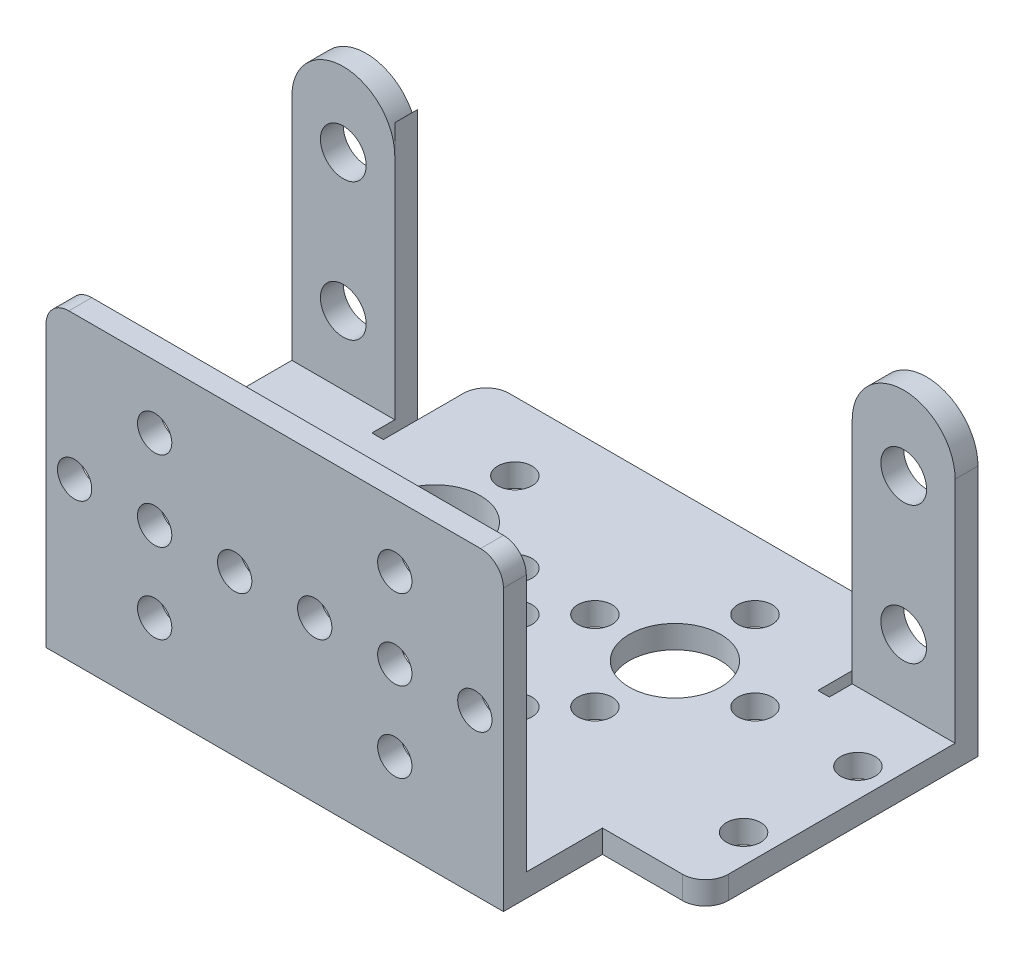
SolidWorks part; units mm, degrees
ref_plane "前视基准面" through (0, 0, 0) normal (0, 0, 1) x (1, 0, 0)
ref_plane "上视基准面" through (0, 0, 0) normal (0, 1, 0) x (1, 0, 0)
ref_plane "右视基准面" through (0, 0, 0) normal (1, 0, 0) x (0, 0, -1)
sketch "草图1" plane through (0, 0, 0) normal (0, 1, 0) x (1, 0, 0)
  line L1 (29, -18.75) -> (-29, -18.75)
  line L2 (29, -18.75) -> (29, 18.75)
  line L3 (29, 18.75) -> (-29, 18.75)
  line L4 (-29, -18.75) -> (-29, 18.75)
  line L5 (29, -18.75) -> (-29, 18.75) construction
  line L6 (29, 18.75) -> (-29, -18.75) construction
  point P0 (0, 0)
  dimension "D1" = 37.5
  dimension "D2" = 58
extrude "凸台-拉伸1" add sketch "草图1" along normal blind 26.5
sketch "草图3" plane through (29, 0, 0) normal (1, 0, 0) x (0, 0, -1)
  line L0 (13.75, 2) -> (22.2889, 2)
  line L2 (-16.75, 2) -> (-16.75, 27.3196)
  line L3 (-16.75, 27.3196) -> (11.75, 27.3196)
  line L4 (11.75, 27.3196) -> (11.75, 2)
  line L7 (13.75, 2) -> (13.75, 26.5)
  line L8 (-18.75, 26.5) -> (18.75, 26.5) construction
  line L9 (13.75, 26.5) -> (22.2889, 26.5)
  line L10 (22.2889, 26.5) -> (22.2889, 2)
  line L14 (-16.75, 2) -> (11.75, 2)
extrude "切除-拉伸1" cut sketch "草图3" against normal through all
sketch "草图4" plane through (0, 2, 0) normal (0, 1, 0) x (1, 0, 0)
  line L0 (-29, 13.75) -> (-20, 13.75)
  line L1 (-29, 18.75) -> (29, 18.75)
  line L2 (29, 18.75) -> (29, 13.75)
  line L3 (0, 23.209) -> (0, -24.1178) construction
  line L6 (-29, -16.75) -> (-29, 11.75) construction
  line L8 (-20, 13.75) -> (-20, 9.75)
  line L9 (-20, 9.75) -> (-19, 9.75)
  line L10 (-19, 9.75) -> (-19, 16.75)
  line L11 (-29, 18.75) -> (29, 18.75) construction
  line L12 (-17, 18.75) -> (17, 18.75)
  line L13 (19, 16.75) -> (19, 9.75)
  line L14 (19, 9.75) -> (20, 9.75)
  line L15 (20, 9.75) -> (20, 13.75)
  line L16 (-29, 13.75) -> (29, 13.75) construction
  line L17 (20, 13.75) -> (29, 13.75)
  line L18 (-29, 13.75) -> (-29, 18.75)
  line L23 (20, -10.0868) -> (27, -10.0868)
  line L24 (-20, -10.0868) -> (-20, -21.4924)
  line L26 (-20, -10.0868) -> (-27, -10.0868)
  line L27 (-20, -21.4924) -> (-29, -21.4924)
  line L28 (-29, -21.4924) -> (-29, -8.0868)
  line L29 (20, -10.0868) -> (20, -21.4924)
  line L30 (20, -21.4924) -> (29, -21.4924)
  line L31 (29, -21.4924) -> (29, -8.0868)
  arc A0 (17, 18.75) -> (19, 16.75) centre (17, 16.75) cw
  arc A1 (-19, 16.75) -> (-17, 18.75) centre (-17, 16.75) cw
  arc A2 (-27, -10.0868) -> (-29, -8.0868) centre (-27, -8.0868) cw
  arc A3 (27, -10.0868) -> (29, -8.0868) centre (27, -8.0868) ccw
  circle A4 centre (-26.5, 5.75) radius 1.5
  circle A5 centre (0, -4.75) radius 4
  circle A6 centre (-26.5, -4.25) radius 1.5
  circle A8 centre (10.5, 5.75) radius 4
  circle A10 centre (7, -4.75) radius 1.5
  circle A11 centre (0, 2.25) radius 1.5
  circle A12 centre (-7, -4.75) radius 1.5
  circle A13 centre (0, -11.75) radius 1.5
  circle A14 centre (10.5, -1.25) radius 1.5
  circle A15 centre (3.5, 5.75) radius 1.5
  circle A16 centre (17.5, 5.75) radius 1.5
  circle A17 centre (10.5, 12.75) radius 1.5
  circle A18 centre (26.5, -4.25) radius 1.5
  circle A19 centre (26.5, 5.75) radius 1.5
  circle A20 centre (-10.5, -1.25) radius 1.5
  circle A21 centre (-17.5, 5.75) radius 1.5
  circle A22 centre (-10.5, 12.75) radius 1.5
  circle A23 centre (-3.5, 5.75) radius 1.5
  circle A24 centre (-10.5, 5.75) radius 4
  point P8 (-29, -4.25)
  point P14 (0, -4.75)
  point P15 (0, -4.25)
  point P32 (19, 18.75)
  point P35 (-19, 18.75)
  point P43 (-29, 5.75)
  point P57 (-26.5, 5.75)
  point P58 (-26.5, -4.25)
  point P70 (10.5, 5.75)
  line M3 (29, 11.75) -> (-29, 11.75)
  dimension "D1" = 2
  dimension "D3" = 2
  dimension "D2" = 3
  dimension "D4" = 7
  dimension "D5" = 7
  dimension "D6" = 7
  dimension "D7" = 7
  dimension "D8" = 7
extrude "切除-拉伸2" cut sketch "草图4" against normal blind 26 and the other way through all contours L10 A1 L1 L18 L0 L8 M3 | L1 A0 L13 L15 L17 L2 M3 | L9 L10 L8 M3 | L14 L15 L13 M3 | L30 L31 A3 L23 L29 | L27 L28 A2 L26 L24 | A24 | A5 | A8
sketch "草图5" plane through (0, 0, -13.75) normal (0, 0, -1) x (-1, 0, 0)
  line L1 (-19, 26.5) -> (19, 26.5)
  line L2 (-19, 26.5) -> (-19, 2)
  line L3 (-19, 2) -> (19, 2)
  line L4 (19, 26.5) -> (19, 2)
extrude "切除-拉伸3" cut sketch "草图5" against normal blind 26
sketch "草图6" plane through (0, 2, 0) normal (0, 1, 0) x (1, 0, 0)
  circle A0 centre (-26.5, 5.75) radius 1.5
  circle A1 centre (-26.5, -4.25) radius 1.5
  circle A2 centre (-17.5, 5.75) radius 1.5
  circle A3 centre (-10.5, 12.75) radius 1.5
  circle A4 centre (10.5, 12.75) radius 1.5
  circle A5 centre (-3.5, 5.75) radius 1.5
  circle A6 centre (0, 2.25) radius 1.5
  circle A7 centre (3.5, 5.75) radius 1.5
  circle A8 centre (-10.5, -1.25) radius 1.5
  circle A9 centre (-7, -4.75) radius 1.5
  circle A10 centre (0, -11.75) radius 1.5
  circle A11 centre (7, -4.75) radius 1.5
  circle A12 centre (10.5, -1.25) radius 1.5
  circle A13 centre (17.5, 5.75) radius 1.5
  circle A14 centre (26.5, 5.75) radius 1.5
  circle A15 centre (26.5, -4.25) radius 1.5
extrude "切除-拉伸4" cut sketch "草图6" against normal through all
sketch "草图7" plane through (0, 0, -13.75) normal (0, 0, -1) x (-1, 0, 0)
  line L0 (0, 30.6383) -> (0, -6.8929) construction
  line L1 (0, 2) -> (0, 14) construction
  line L2 (17, 2) -> (-17, 2) construction
  line L3 (-42.2035, 14) -> (34.7183, 14) construction
  line L4 (-20, 0) -> (-20, 26.5) construction
  line L5 (-20, 14) -> (-17.5, 14)
  line L6 (-17.5, 14) -> (-10.5, 14)
  line L7 (-10.5, 14) -> (-3.5, 14)
  line L8 (-10.5, 14) -> (-10.5, 21) construction
  line L9 (-20, 14) -> (-20, 2)
  line L11 (-29, 26.5) -> (-18, 26.5)
  line L12 (18, 26.5) -> (29, 26.5)
  line L13 (-20, 24.5) -> (-20, 22)
  line L14 (29, 26.5) -> (29.0023, 22)
  line L15 (20, 14) -> (20, 2)
  line L16 (20, 24.5) -> (20.0023, 22)
  line L18 (-29, 26.5) -> (-29, 22)
  line L19 (-20, 22) -> (-20, 24.5)
  circle A0 centre (-17.5, 14) radius 1.5
  circle A1 centre (-10.5, 14) radius 1.5
  circle A2 centre (-3.5, 14) radius 1.5
  circle A3 centre (-10.5, 21) radius 1.5
  circle A4 centre (-10.5, 7) radius 1.5
  circle A5 centre (-24.5023, 20) radius 2
  circle A6 centre (-24.5023, 8) radius 2
  circle A7 centre (10.5, 7) radius 1.5
  circle A8 centre (3.5, 14) radius 1.5
  circle A9 centre (10.5, 14) radius 1.5
  circle A10 centre (10.5, 21) radius 1.5
  circle A11 centre (17.5, 14) radius 1.5
  circle A12 centre (24.5023, 8) radius 2
  circle A13 centre (24.5023, 20) radius 2
  arc A14 (-20, 22) -> (-29, 22) centre (-24.5, 22) ccw
  arc A15 (20, 24.5) -> (18, 26.5) centre (18, 24.5) ccw
  arc A16 (-20, 24.5) -> (-18, 26.5) centre (-18, 24.5) cw
  arc A17 (29.0023, 22) -> (20.0023, 22) centre (24.5023, 22) ccw
  point P9 (-20, 14)
  point P54 (-20, 26.5)
  line M6 (-29, 26.5) -> (-29, 0)
  line M8 (-20, 0) -> (-20, 26.5)
  line M9 (-20, 26.5) -> (-29, 26.5)
  dimension "D2" = 2.5
  dimension "D4" = 12
  dimension "D5" = 2
  dimension "D1" = 7
  dimension "D3" = 7
extrude "切除-拉伸5" cut sketch "草图7" against normal through all contours A14 L11 M6 | A14 M8 M9 | A5 | A6 | A16 L11 M8 | A17 L12 A15 L16 | A17 L14 L12 | A13 | A10 | A4 | A8 | A9 | A11 | A12 | A7 | A0 | A1 | A3 | A2
